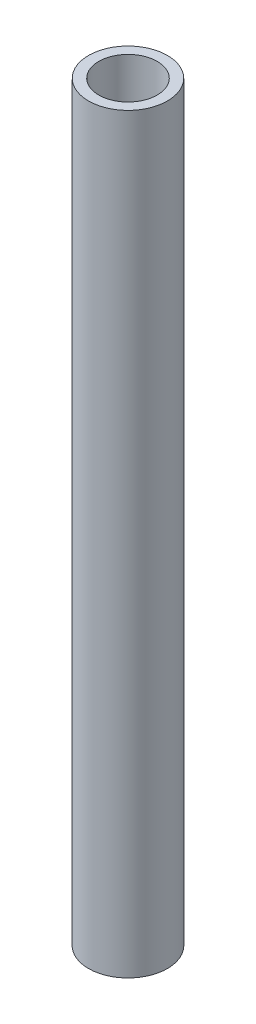
SolidWorks part; units mm, degrees
material "PVC Rigid"
ref_plane "Front Plane" through (0, 0, 0) normal (0, 0, 1) x (1, 0, 0)
ref_plane "Top Plane" through (0, 0, 0) normal (0, 1, 0) x (1, 0, 0)
ref_plane "Right Plane" through (0, 0, 0) normal (1, 0, 0) x (0, 0, -1)
sketch "Sketch1" plane through (0, 0, 0) normal (0, 1, 0) x (1, 0, 0)
  circle A0 centre (0, 0) radius 10.668
  circle A1 centre (0, 0) radius 7.8994
  dimension "D1" = 21.336
  dimension "D2" = 15.7988
  dimension "D3" = 2.7686
extrude "Boss-Extrude1" add sketch "Sketch1" along normal blind 203.2
